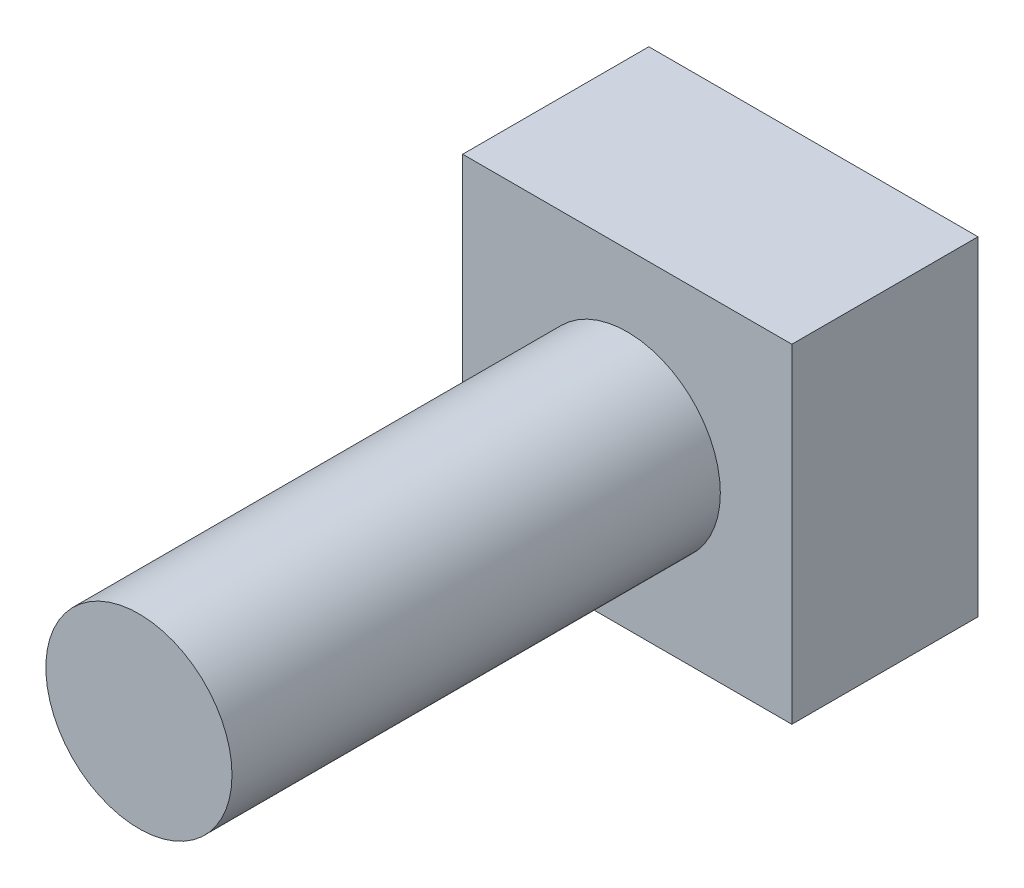
SolidWorks part; units mm, degrees
ref_plane "Front Plane" through (0, 0, 0) normal (0, 0, 1) x (1, 0, 0)
ref_plane "Top Plane" through (0, 0, 0) normal (0, 1, 0) x (1, 0, 0)
ref_plane "Right Plane" through (0, 0, 0) normal (1, 0, 0) x (0, 0, -1)
sketch "Sketch1" plane through (0, 0, 0) normal (0, 0, 1) x (1, 0, 0)
  line L1 (3.0988, -3.0988) -> (-3.0988, -3.0988)
  line L2 (3.0988, -3.0988) -> (3.0988, 3.0988)
  line L3 (3.0988, 3.0988) -> (-3.0988, 3.0988)
  line L4 (-3.0988, -3.0988) -> (-3.0988, 3.0988)
  line L5 (3.0988, -3.0988) -> (-3.0988, 3.0988) construction
  line L6 (3.0988, 3.0988) -> (-3.0988, -3.0988) construction
  point P0 (0, 0)
  dimension "D1" = 6.1976
  dimension "D2" = 6.1976
extrude "Boss-Extrude1" add sketch "Sketch1" against normal blind 3.5052
sketch "Sketch2" plane through (0, 0, 0) normal (0, 0, 1) x (1, 0, 0)
  circle A0 centre (0, 0) radius 1.7526
  dimension "D1" = 3.5052
extrude "Boss-Extrude2" add sketch "Sketch2" along normal blind 9.1948
